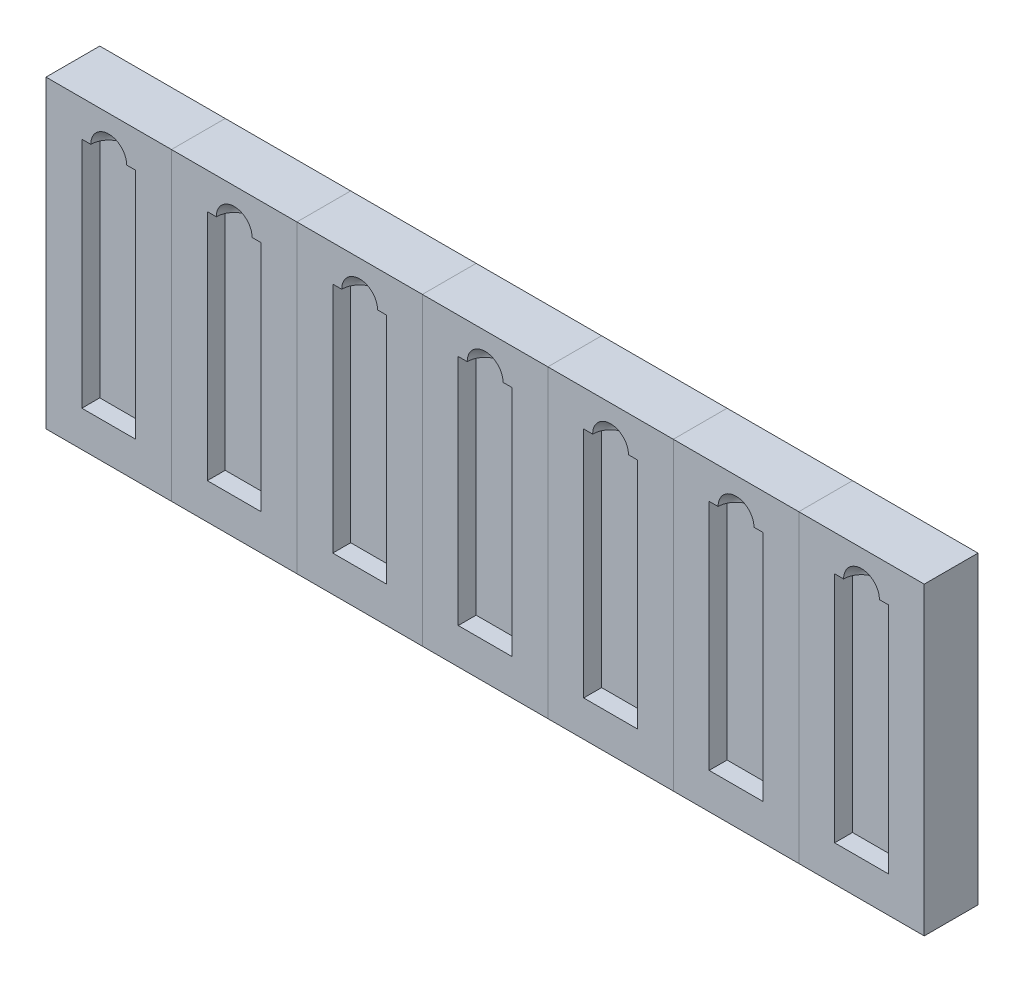
SolidWorks part; units mm, degrees
ref_plane "Front Plane" through (0, 0, 0) normal (0, 0, 1) x (1, 0, 0)
ref_plane "Top Plane" through (0, 0, 0) normal (0, 1, 0) x (1, 0, 0)
ref_plane "Right Plane" through (0, 0, 0) normal (1, 0, 0) x (0, 0, -1)
sketch "Sketch1" plane through (0, 0, 0) normal (0, 0, 1) x (1, 0, 0)
  line L1 (-3.5, 8.5) -> (3.5, 8.5)
  line L2 (-3.5, 8.5) -> (-3.5, -8.5)
  line L3 (-3.5, -8.5) -> (3.5, -8.5)
  line L4 (3.5, 8.5) -> (3.5, -8.5)
  line L5 (-3.5, 8.5) -> (3.5, -8.5) construction
  line L6 (-3.5, -8.5) -> (3.5, 8.5) construction
  point P0 (0, 0)
  dimension "D1" = 17
  dimension "D2" = 7
extrude "Boss-Extrude1" add sketch "Sketch1" along normal blind 3
shell "Shell1" thickness 2
sketch "Sketch2" plane through (0, 0, 3) normal (0, 0, 1) x (1, 0, 0)
  line L0 (1.5, 6.5) -> (-1.5, 6.5) construction
  line L1 (-1, 6.5) -> (1, 6.5) construction
  line L2 (-1, 6.5) -> (1, 6.5)
  arc A0 (1, 6.5) -> (-1, 6.5) centre (0, 6.5) ccw
  dimension "D1" = 2
revolve "Cut-Revolve1" cut sketch "Sketch2" angle 360 about L1
pattern_linear "LPattern1" count 7 spacing 7 along (1, 0, 0) of bodies 108 101
